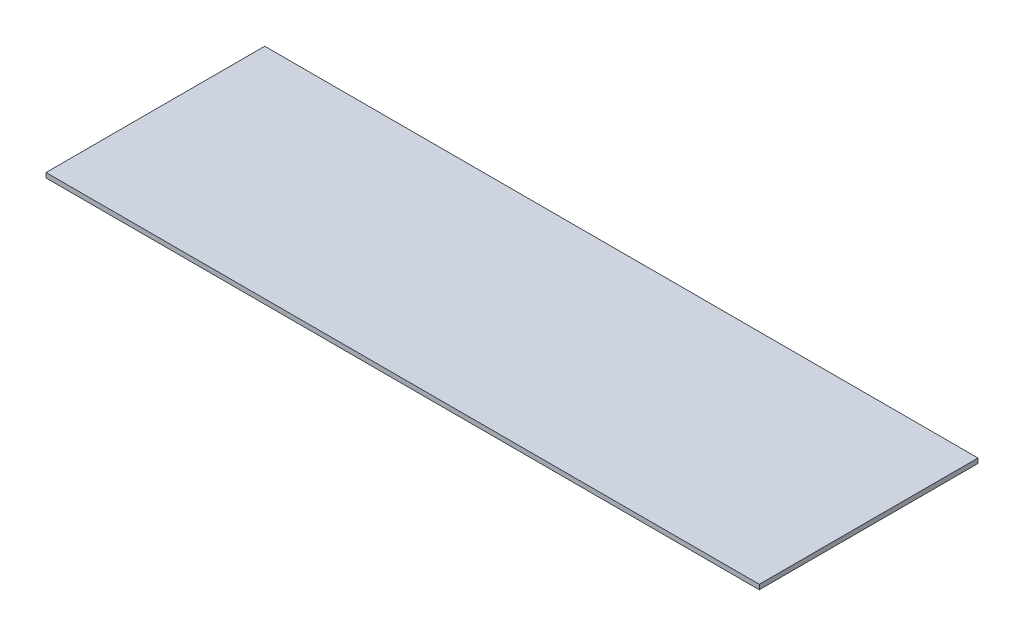
SolidWorks part; units mm, degrees
material "A-Glass Fiber"
ref_plane "Front Plane" through (0, 0, 0) normal (0, 0, 1) x (1, 0, 0)
ref_plane "Top Plane" through (0, 0, 0) normal (0, 1, 0) x (1, 0, 0)
ref_plane "Right Plane" through (0, 0, 0) normal (1, 0, 0) x (0, 0, -1)
sketch "Sketch1" plane through (0, 0, 0) normal (0, 1, 0) x (1, 0, 0)
  line L1 (-89.1211, 55.7339) -> (387.1289, 55.7339)
  line L2 (-89.1211, 55.7339) -> (-89.1211, -90.3161)
  line L3 (-89.1211, -90.3161) -> (387.1289, -90.3161)
  line L4 (387.1289, 55.7339) -> (387.1289, -90.3161)
  dimension "D1" = 476.25
  dimension "D2" = 146.05
extrude "Boss-Extrude1" add sketch "Sketch1" along normal blind 3.175
